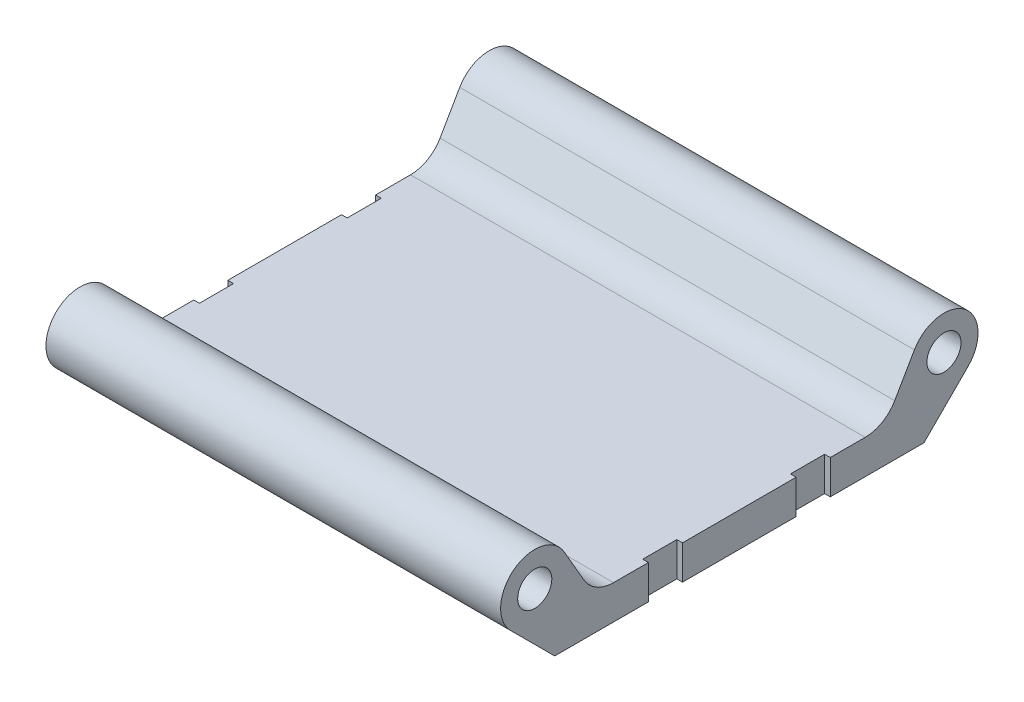
SolidWorks part; units mm, degrees
ref_plane "정면" through (0, 0, 0) normal (0, 0, 1) x (1, 0, 0)
ref_plane "윗면" through (0, 0, 0) normal (0, 1, 0) x (1, 0, 0)
ref_plane "우측면" through (0, 0, 0) normal (1, 0, 0) x (0, 0, -1)
sketch "스케치1" plane through (0, 0, 0) normal (1, 0, 0) x (0, 0, -1)
  line L0 (0, 0) -> (0, 7.6904) construction
  line L1 (-15.4019, 7.5) -> (-12.8038, 3)
  line L2 (15.4019, 7.5) -> (12.8038, 3)
  line L3 (-12.8038, 3) -> (12.8038, 3)
  line L4 (-20.1213, 3.8787) -> (-16.2426, 0)
  line L5 (20.1213, 3.8787) -> (16.2426, 0)
  line L6 (-16.2426, 0) -> (0, 0)
  line L7 (16.2426, 0) -> (0, 0)
  circle A0 centre (18, 6) radius 1.5
  circle A1 centre (-18, 6) radius 1.5
  arc A2 (-15.4019, 7.5) -> (-20.1213, 3.8787) centre (-18, 6) ccw
  arc A3 (15.4019, 7.5) -> (20.1213, 3.8787) centre (18, 6) cw
  point P14 (0, 3)
  dimension "D1" = 3
  dimension "D3" = 3
  dimension "D2" = 36
  dimension "D4" = 3
  dimension "D5" = 120
  dimension "D6" = 135
  dimension "D7" = 6
extrude "보스-돌출1" add sketch "스케치1" along normal blind 40
fillet "필렛1" radius 3 2 edges at (20, 3, -12.8038) (20, 3, 12.8038)
sketch "스케치2" plane through (0, 3, 0) normal (0, 1, 0) x (1, 0, 0)
  line L0 (20, 11.0718) -> (20, -11.0718) construction
  line L1 (40, 8) -> (40, 5)
  line L2 (0, 8) -> (0.5, 8)
  line L3 (0, 8) -> (0, 5)
  line L4 (40, -11.0718) -> (40, 11.0718)
  line L5 (40, 11.0718) -> (0, 11.0718)
  line L6 (0, 11.0718) -> (0, -11.0718)
  line L7 (0, -11.0718) -> (40, -11.0718)
  line L8 (40, -11.0718) -> (40, 11.0718)
  line L9 (40, 11.0718) -> (0, 11.0718)
  line L10 (0, 11.0718) -> (0, -11.0718)
  line L11 (0, -11.0718) -> (40, -11.0718)
  line L12 (0, 5) -> (0.5, 5)
  line L13 (0.5, 8) -> (0.5, 5)
  line L14 (40, 8) -> (39.5, 8)
  line L15 (39.5, 8) -> (39.5, 5)
  line L16 (40, 5) -> (39.5, 5)
  line L17 (0, 0) -> (40, 0) construction
  line L18 (40, -8) -> (40, -5)
  line L19 (40, -5) -> (39.5, -5)
  line L20 (40, -8) -> (39.5, -8)
  line L21 (39.5, -8) -> (39.5, -5)
  line L22 (0.5, -8) -> (0.5, -5)
  line L23 (0, -5) -> (0.5, -5)
  line L24 (0, -8) -> (0.5, -8)
  line L25 (0, -8) -> (0, -5)
  line M14 (40, -11.0718) -> (40, 11.0718)
  line M16 (0, 11.0718) -> (0, -11.0718)
  dimension "D2" = 3
  dimension "D3" = 0.5
  dimension "D4" = 10
  dimension "D1" = 0
extrude "컷-돌출1" cut sketch "스케치2" against normal through all contours L13 L2 L12 M16 | L10 L24 L22 L23 | L16 L14 L15 M14 | L21 L19 L18 L20
